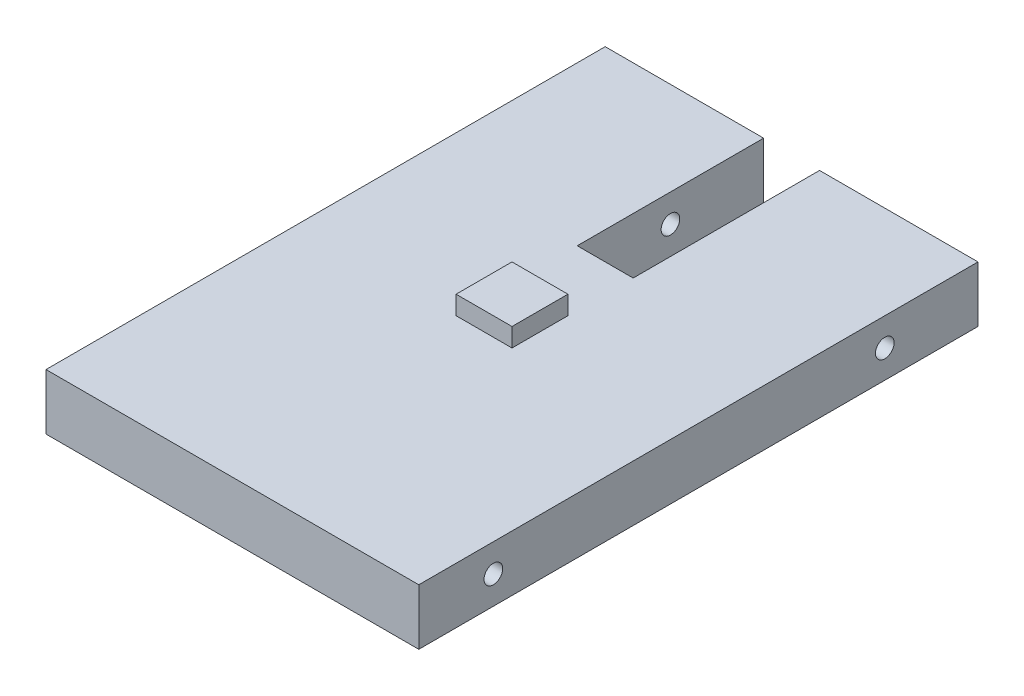
SolidWorks part; units mm, degrees
ref_plane "前基準面" through (0, 0, 0) normal (0, 0, 1) x (1, 0, 0)
ref_plane "上基準面" through (0, 0, 0) normal (0, 1, 0) x (1, 0, 0)
ref_plane "右基準面" through (0, 0, 0) normal (1, 0, 0) x (0, 0, -1)
sketch "草圖1" plane through (0, 0, 0) normal (0, 1, 0) x (1, 0, 0)
  line L0 (0, 0) -> (0, 199.7027) construction
  line L1 (-100, -150) -> (100, -150)
  line L2 (-100, -150) -> (-100, 150)
  line L3 (-100, 150) -> (-15, 150)
  line L4 (100, -150) -> (100, 150)
  line L5 (-100, -150) -> (100, 150) construction
  line L6 (-100, 150) -> (100, -150) construction
  line L7 (-15, 150) -> (-15, 50)
  line L8 (-15, 50) -> (15, 50)
  line L9 (15, 50) -> (15, 150)
  line L10 (15, 150) -> (100, 150)
  point P0 (0, 0)
  dimension "D1" = 300
  dimension "D2" = 200
  dimension "D3" = 30
  dimension "D4" = 100
extrude "填料-伸長1" add sketch "草圖1" along normal blind 30
sketch "草圖2" plane through (-100, 0, 0) normal (-1, 0, 0) x (0, 0, 1)
  line L0 (-150, 15) -> (150, 15) construction
  line L1 (-150, 30) -> (-150, 0) construction
  line L2 (150, 30) -> (150, 0) construction
  circle A0 centre (-100, 15) radius 5
  circle A1 centre (110, 15) radius 5
  dimension "D1" = 10
  dimension "D2" = 10
  dimension "D3" = 50
  dimension "D4" = 40
extrude "除料-伸長1" cut sketch "草圖2" against normal blind 335
sketch "草圖3" plane through (0, 30, 0) normal (0, 1, 0) x (1, 0, 0)
  line L1 (-15, -15) -> (15, -15)
  line L2 (-15, -15) -> (-15, 15)
  line L3 (-15, 15) -> (15, 15)
  line L4 (15, -15) -> (15, 15)
  line L5 (-15, -15) -> (15, 15) construction
  line L6 (-15, 15) -> (15, -15) construction
  point P0 (0, 0)
  dimension "D1" = 30
  dimension "D2" = 30
extrude "填料-伸長2" add sketch "草圖3" along normal blind 10
